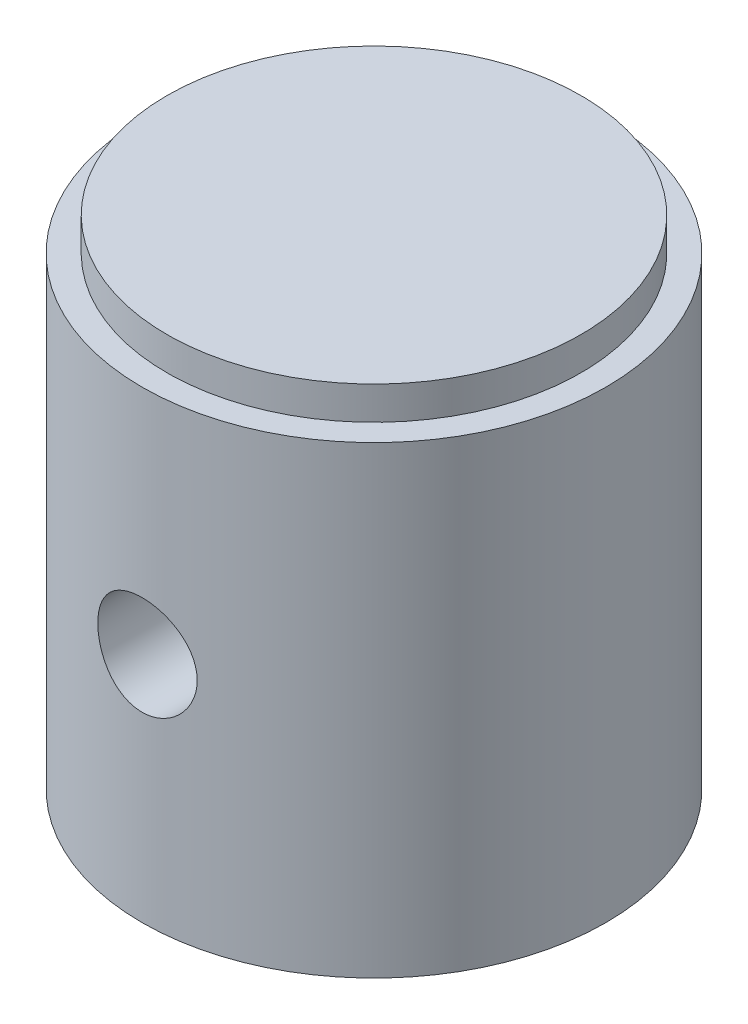
SolidWorks part; units mm, degrees
ref_plane "Front Plane" through (0, 0, 0) normal (0, 0, 1) x (1, 0, 0)
ref_plane "Top Plane" through (0, 0, 0) normal (0, 1, 0) x (1, 0, 0)
ref_plane "Right Plane" through (0, 0, 0) normal (1, 0, 0) x (0, 0, -1)
sketch "Sketch1" plane through (0, 0, 0) normal (0, 0, 1) x (1, 0, 0)
  line L0 (0, 1.1459) -> (0, -6.3) construction
  line L1 (0, 1.1459) -> (-6.25, 1.1459)
  line L2 (-6.25, 1.1459) -> (-6.25, 0.1459)
  line L3 (-6.25, 0.1459) -> (-7, 0.1459)
  line L4 (-7, 0.1459) -> (-7, -13.8541)
  line L5 (-7, -13.8541) -> (-6.25, -13.8541)
  line L6 (-6.25, -13.8541) -> (-4.75, -9.7329)
  line L7 (-4.75, -9.7329) -> (-4.75, -2.8541)
  line L8 (-4.75, -2.8541) -> (0, 0)
  line L9 (0, 0) -> (0, 1.1459)
  dimension "D1" = 7
  dimension "D2" = 6.25
  dimension "D3" = 15
  dimension "D4" = 1
  dimension "D5" = 6.25
  dimension "D6" = 4.75
  dimension "D7" = 20
  dimension "D8" = 59
  dimension "D9" = 11
revolve "Revolve1" add sketch "Sketch1" angle 360 about L0
sketch "Sketch2" plane through (0, 0, 0) normal (0, 0, 1) x (1, 0, 0)
  line L0 (-7, -13.8541) -> (7, -13.8541) construction
  circle A0 centre (0, -6.8541) radius 1.5
  dimension "D1" = 3
  dimension "D2" = 7
extrude "Cut-Extrude1" cut sketch "Sketch2" against normal through all both and the other way through all
